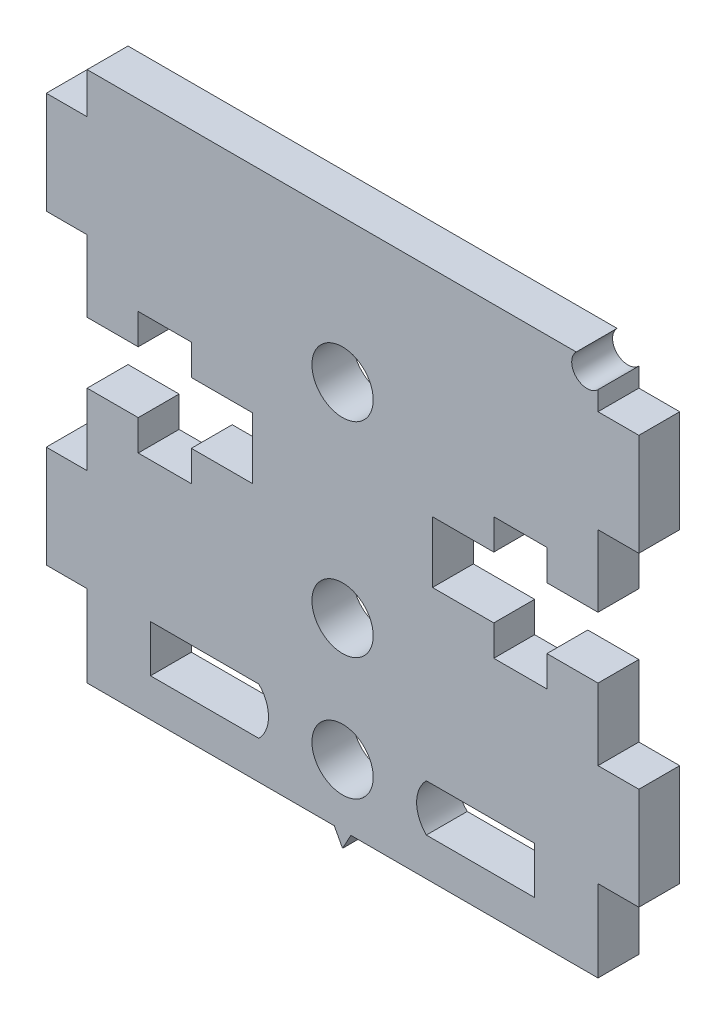
SolidWorks part; units mm, degrees
ref_plane "前视基准面" through (0, 0, 0) normal (0, 0, 1) x (1, 0, 0)
ref_plane "上视基准面" through (0, 0, 0) normal (0, 1, 0) x (1, 0, 0)
ref_plane "右视基准面" through (0, 0, 0) normal (1, 0, 0) x (0, 0, -1)
sketch "草图1" plane through (0, 0, 0) normal (0, 0, 1) x (1, 0, 0)
  line L8 (-5.4329, -11.201) -> (-0.4329, -11.201) construction
  line L38 (18.3171, 8.799) -> (16.3171, 8.799)
  line L39 (18.3171, 3.799) -> (18.3171, 8.799)
  line L40 (16.3171, 3.799) -> (18.3171, 3.799)
  line L42 (18.3171, -6.201) -> (16.3171, -6.201)
  line L47 (16.3171, -11.201) -> (16.3171, -15.201)
  line L48 (18.3171, -11.201) -> (18.3171, -6.201)
  line L49 (16.3171, -11.201) -> (18.3171, -11.201)
  line L55 (13.0671, -11.201) -> (8.0671, -11.201) construction
  line L57 (13.2171, -13.3428) -> (7.9171, -13.3428)
  line L58 (13.2171, -11.0428) -> (13.2171, -13.3428)
  line L63 (-8.6829, -2.701) -> (-8.6829, -6.201)
  line L64 (-6.1829, -2.701) -> (-8.6829, -2.701)
  line L65 (-8.6829, 0.299) -> (-8.6829, 3.799)
  line L66 (13.2171, -11.0428) -> (7.9171, -11.0428)
  line L71 (13.0671, -11.0428) -> (13.2171, -11.0428)
  line L72 (13.0671, -11.201) -> (13.0671, -11.0428)
  line L74 (3.8171, -6.201) -> (3.8171, 3.799) construction
  line L76 (3.8171, -15.9558) -> (4.223, -15.201)
  line L81 (3.8171, -15.9558) -> (3.4111, -15.201)
  line L96 (-6.1829, 0.299) -> (-8.6829, 0.299)
  line L98 (13.8171, 1.799) -> (11.2171, 1.799)
  line L99 (11.2171, 1.799) -> (11.2171, 0.299)
  line L100 (11.2171, 0.299) -> (8.2171, 0.299)
  line L101 (11.2171, -2.701) -> (8.2171, -2.701)
  line L102 (11.2171, -4.201) -> (11.2171, -2.701)
  line L103 (13.8171, -4.201) -> (11.2171, -4.201)
  line L104 (13.8171, 0.299) -> (13.8171, 1.799)
  line L105 (8.2171, 0.299) -> (8.2171, -2.701)
  line L106 (13.8171, -2.701) -> (13.8171, -4.201)
  line L107 (13.8171, 0.299) -> (16.3171, 0.299)
  line L108 (16.3171, 0.299) -> (16.3171, 3.799)
  line L109 (13.8171, -2.701) -> (16.3171, -2.701)
  line L110 (16.3171, -2.701) -> (16.3171, -6.201)
  line L111 (-6.1829, -2.701) -> (-6.1829, -4.201)
  line L112 (-0.5829, 0.299) -> (-0.5829, -2.701)
  line L113 (-6.1829, 0.299) -> (-6.1829, 1.799)
  line L114 (-6.1829, -4.201) -> (-3.5829, -4.201)
  line L115 (-3.5829, -4.201) -> (-3.5829, -2.701)
  line L116 (-3.5829, -2.701) -> (-0.5829, -2.701)
  line L117 (-3.5829, 0.299) -> (-0.5829, 0.299)
  line L118 (-3.5829, 1.799) -> (-3.5829, 0.299)
  line L119 (-6.1829, 1.799) -> (-3.5829, 1.799)
  line L120 (-5.4329, -11.201) -> (-5.4329, -11.0428)
  line L121 (-5.4329, -11.0428) -> (-5.5829, -11.0428)
  line L122 (-5.5829, -11.0428) -> (-0.2829, -11.0428)
  line L123 (-5.5829, -11.0428) -> (-5.5829, -13.3428)
  line L124 (-5.5829, -13.3428) -> (-0.2829, -13.3428)
  line L125 (-8.6829, -11.201) -> (-10.6829, -11.201)
  line L126 (-10.6829, -11.201) -> (-10.6829, -6.201)
  line L127 (-8.6829, -11.201) -> (-8.6829, -15.201)
  line L128 (-10.6829, -6.201) -> (-8.6829, -6.201)
  line L129 (-8.6829, 3.799) -> (-10.6829, 3.799)
  line L130 (-10.6829, 3.799) -> (-10.6829, 8.799)
  line L131 (-10.6829, 8.799) -> (-8.6829, 8.799)
  line L132 (-8.6829, 8.799) -> (-8.6829, 10.799)
  line L134 (16.3171, -15.201) -> (4.223, -15.201)
  line L135 (3.4111, -15.201) -> (-8.6829, -15.201)
  line L136 (16.3171, 9.7336) -> (16.3171, 8.799)
  line L137 (15.2516, 10.799) -> (-8.6829, 10.799)
  circle A6 centre (3.8171, -6.201) radius 1.5
  circle A7 centre (3.8171, 3.799) radius 1.5
  arc A9 (7.9171, -11.0428) -> (7.9171, -13.3428) centre (9.0671, -12.1928) ccw
  circle A10 centre (3.8171, -12.1928) radius 1.5
  arc A11 (-0.2829, -11.0428) -> (-0.2829, -13.3428) centre (-1.4329, -12.1928) cw
  arc A13 (16.3171, 9.7336) -> (15.2516, 10.799) centre (15.7843, 10.2663) cw
extrude "凸台-拉伸1" add sketch "草图1" along normal blind 2
sketch "草图3" plane through (16.3171, 0, 0) normal (1, 0, 0) x (0, 0, -1)
  line L0 (-1, 0.299) -> (-1, -2.701)
  line L1 (-2, 0.299) -> (0, 0.299) construction
  line L2 (-2, -2.701) -> (0, -2.701) construction
  circle A0 centre (-1, -1.201) radius 1.5
sketch "草图4" plane through (-8.6829, 0, 0) normal (-1, 0, 0) x (0, 0, 1)
  line L0 (1, 0.299) -> (1, -2.701)
  line L1 (2, 0.299) -> (0, 0.299) construction
  line L2 (2, -2.701) -> (0, -2.701) construction
  circle A0 centre (1, -1.201) radius 1.5
